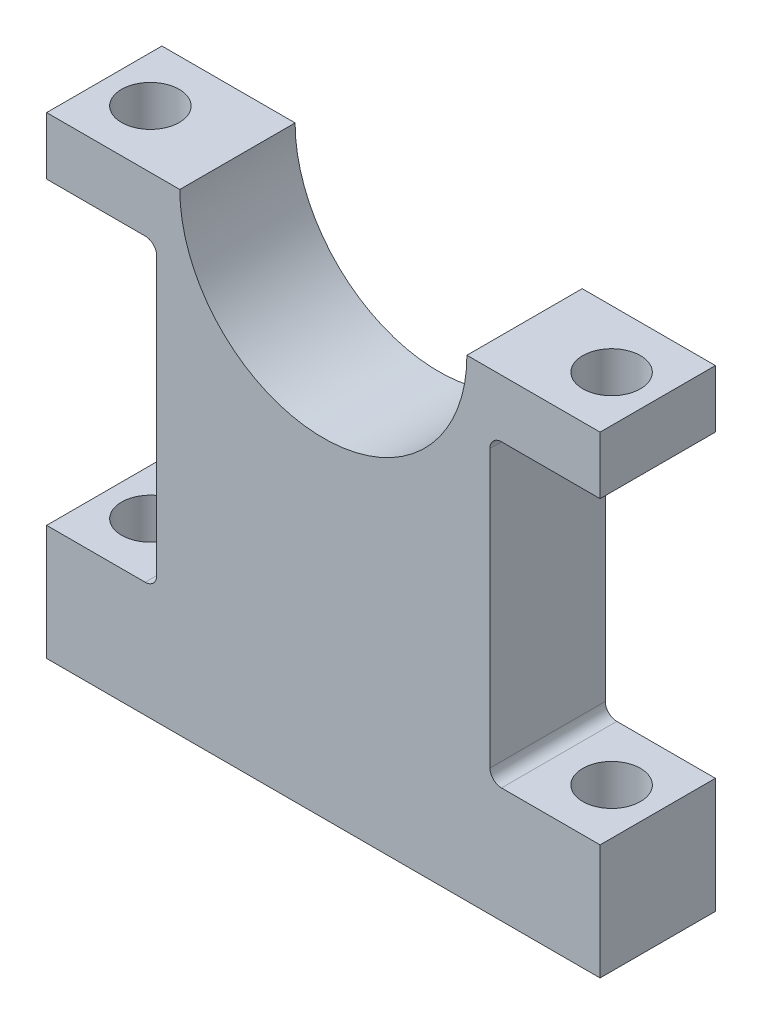
SolidWorks part; units mm, degrees
ref_plane "前视基准面" through (0, 0, 0) normal (0, 0, 1) x (1, 0, 0)
ref_plane "上视基准面" through (0, 0, 0) normal (0, 1, 0) x (1, 0, 0)
ref_plane "右视基准面" through (0, 0, 0) normal (1, 0, 0) x (0, 0, -1)
sketch "草图1" plane through (0, 0, 0) normal (0, 0, 1) x (1, 0, 0)
  line L0 (12.45, 0) -> (12.45, -41)
  line L1 (12.45, -41) -> (-12.45, -41)
  line L2 (-12.45, -41) -> (-12.45, 0)
  arc A0 (-12.45, 0) -> (12.45, 0) centre (0, 0) ccw
  dimension "D1" = 24.9
  dimension "D2" = 41
extrude "凸台-拉伸1" add sketch "草图1" along normal mid plane 10
sketch "草图3" plane through (0, -41, 0) normal (0, -1, 0) x (1, 0, 0)
  line L1 (-24, 5) -> (24, 5)
  line L2 (-24, 5) -> (-24, -5)
  line L3 (-24, -5) -> (24, -5)
  line L4 (24, 5) -> (24, -5)
  line L5 (0, -5) -> (0, 5) construction
  line L6 (-24, 0) -> (24, 0) construction
  circle A0 centre (20, 0) radius 2.5
  circle A1 centre (-20, 0) radius 2.5
  point P0 (0, 0)
  dimension "D3" = 5
  dimension "D1" = 10
  dimension "D2" = 48
  dimension "D4" = 20
extrude "凸台-拉伸2" add sketch "草图3" against normal blind 10
sketch "草图4" plane through (0, 0, 0) normal (0, 1, 0) x (1, 0, 0)
  line L1 (-24, 5) -> (24, 5)
  line L2 (-24, 5) -> (-24, -5)
  line L3 (-24, -5) -> (24, -5)
  line L4 (24, 5) -> (24, -5)
  line L5 (0, -5) -> (0, 5) construction
  line L6 (-24, 0) -> (24, 0) construction
  circle A0 centre (-20, 0) radius 2.5
  circle A1 centre (20, 0) radius 2.5
  point P0 (0, 0)
extrude "凸台-拉伸3" add sketch "草图4" against normal blind 5
sketch "草图5" plane through (0, 0, 5) normal (0, 0, 1) x (1, 0, 0)
  line L0 (-12.45, -31) -> (-24, -31) construction
  line L1 (-12.45, -5) -> (-14.45, -5)
  line L2 (-12.45, -5) -> (-12.45, -31)
  line L3 (-12.45, -31) -> (-14.45, -31)
  line L4 (-14.45, -5) -> (-14.45, -31)
  line L5 (0, 0) -> (0, -10.3273) construction
  line L6 (12.45, -31) -> (14.45, -31)
  line L7 (14.45, -5) -> (14.45, -31)
  line L8 (12.45, -5) -> (14.45, -5)
  line L9 (12.45, -5) -> (12.45, -31)
  dimension "D1" = 2
extrude "凸台-拉伸4" add sketch "草图5" against normal up to surface (10 mm away) up to face at (0, -18.8333, -5)
sketch "草图6" plane through (0, 0, 5) normal (0, 0, 1) x (1, 0, 0)
  circle A0 centre (0, 0) radius 12.45
  dimension "D1" = 24.9
extrude "切除-拉伸1" cut sketch "草图6" against normal blind 16
fillet "圆角2" radius 1 2 edges at (14.45, -31, 0) (-14.45, -31, 0)
fillet "圆角3" radius 1 2 edges at (14.45, -5, 0) (-14.45, -5, 0)
